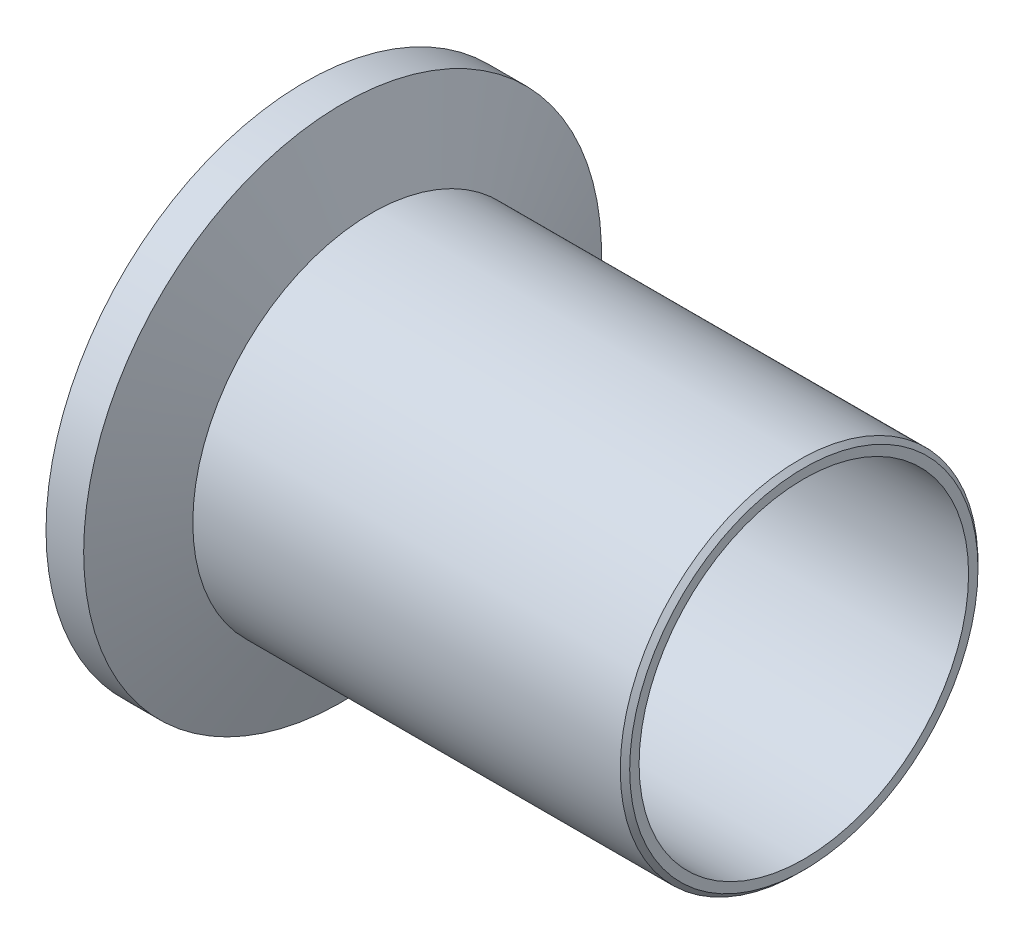
SolidWorks part; units mm, degrees
ref_plane "정면" through (0, 0, 0) normal (0, 0, 1) x (1, 0, 0)
ref_plane "윗면" through (0, 0, 0) normal (0, 1, 0) x (1, 0, 0)
ref_plane "우측면" through (0, 0, 0) normal (1, 0, 0) x (0, 0, -1)
sketch "스케치1" plane through (0, 0, 0) normal (0, 0, 1) x (1, 0, 0)
  line L0 (0, 17.5) -> (0, 27.5)
  line L1 (0, 27.5) -> (4, 27.5)
  line L2 (4, 27.5) -> (7.0937, 19)
  line L3 (7.0937, 19) -> (53, 19)
  line L4 (53, 19) -> (53, 17.5)
  line L5 (53, 17.5) -> (0, 17.5)
  line L6 (0, 0) -> (62.4884, 0) construction
  dimension "D1" = 35
  dimension "D2" = 38
  dimension "D3" = 53
  dimension "D4" = 110
  dimension "D5" = 55
  dimension "D6" = 4
revolve "회전1" add sketch "스케치1" angle 360 about L6
sketch "스케치2" plane through (0, 0, 0) normal (-1, 0, 0) x (0, 0, 1)
  circle A0 centre (0, 0) radius 20.5
  dimension "D1" = 41
extrude "컷-돌출1" cut sketch "스케치2" against normal blind 3
sketch "스케치3" plane through (3, 0, 0) normal (-1, 0, 0) x (0, 0, 1)
  circle A0 centre (0, 0) radius 18
  dimension "D1" = 36
extrude "컷-돌출2" cut sketch "스케치3" against normal blind 0.5
chamfer "모따기1" distance 0.5 angle 45 1 edges at (53, 0, 19)
